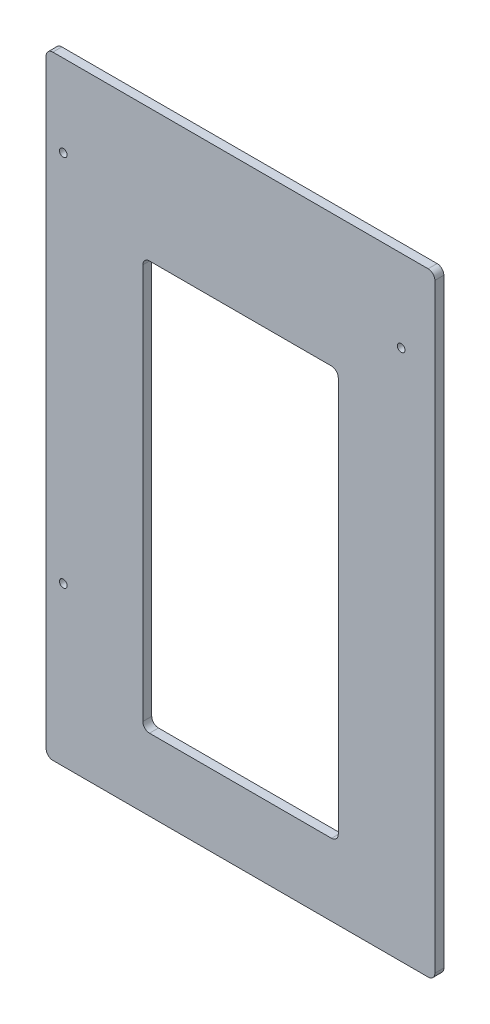
SolidWorks part; units mm, degrees
material "Verre"
ref_plane "Plan de face" through (0, 0, 0) normal (0, 0, 1) x (1, 0, 0)
ref_plane "Plan de dessus" through (0, 0, 0) normal (0, 1, 0) x (1, 0, 0)
ref_plane "Plan de droite" through (0, 0, 0) normal (1, 0, 0) x (0, 0, -1)
sketch "Esquisse1" plane through (0, 0, 0) normal (0, 0, 1) x (1, 0, 0)
  line L1 (0, 0) -> (173, 0)
  line L2 (0, 0) -> (0, 273)
  line L3 (0, 273) -> (173, 273)
  line L4 (173, 0) -> (173, 273)
  line L5 (43, 32) -> (130, 32)
  line L6 (43, 32) -> (43, 214)
  line L7 (43, 214) -> (130, 214)
  line L8 (130, 32) -> (130, 214)
  circle A0 centre (7.62, 236.5) radius 1.5
  circle A1 centre (7.62, 70.5) radius 1.5
  circle A2 centre (158, 236.5) radius 1.5
  dimension "D8" = 3
  dimension "D10" = 3
  dimension "D14" = 3
  dimension "D1" = 173
  dimension "D2" = 273
  dimension "D3" = 43
  dimension "D4" = 87
  dimension "D5" = 182
  dimension "D6" = 32
  dimension "D7" = 7.62
  dimension "D9" = 7.62
  dimension "D11" = 36.5
  dimension "D12" = 70.5
  dimension "D13" = 36.5
  dimension "D15" = 15
extrude "Boss.-Extru.1" add sketch "Esquisse1" along normal blind 4
fillet "Congé1" radius 3 8 edges at (0, 0, 2) (173, 0, 2) (173, 273, 2) (0, 273, 2) (43, 32, 2) (130, 32, 2) (130, 214, 2) (43, 214, 2)
hole_wizard "Dégagement M31" positions "Esquisse2" profile "Esquisse3" hole size "M3" standard "ISO" end condition through all
sketch "Esquisse2" plane through (0, 0, 4) normal (0, 0, 1) x (1, 0, 0)
  point P0 (7.62, 236.5)
  point P3 (7.62, 70.5)
  point P6 (158, 236.5)
sketch "Esquisse3" plane through (7.62, 236.5, 4) normal (1, 0, 0) x (0, -1, 0)
  line L0 (0, 0) -> (0, 4)
  line L1 (0, 4) -> (1.7, 4)
  line L2 (1.7, 4) -> (1.7, 0)
  line L5 (1.7, 0) -> (0, 0)
  line L11 (0, -6.35) -> (0, 107.95) construction
  dimension "Diamètre du perçage jusqu'au prochain" = 3.4
  dimension "Profondeur du perçage jusqu'au prochain" = 4
